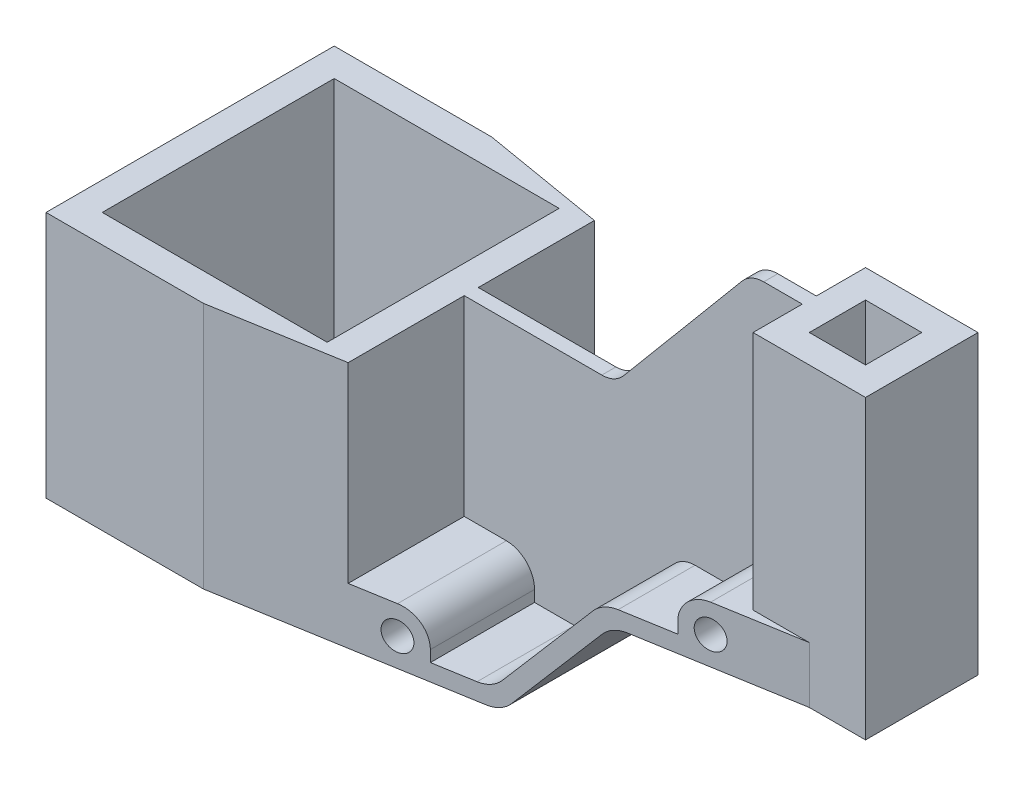
SolidWorks part; units mm, degrees
material "Alliage 1060"
ref_plane "Front Plane" through (0, 0, 0) normal (0, 0, 1) x (1, 0, 0)
ref_plane "Top Plane" through (0, 0, 0) normal (0, 1, 0) x (1, 0, 0)
ref_plane "Right Plane" through (0, 0, 0) normal (1, 0, 0) x (0, 0, -1)
sketch "Esquisse1" plane through (0, 0, 0) normal (0, 1, 0) x (1, 0, 0)
  line L0 (0, 0) -> (251.0912, 0) construction
  line L1 (-50, 51.25) -> (50, 51.25)
  line L2 (-50, 51.25) -> (-50, -51.25)
  line L3 (-50, -51.25) -> (50, -51.25)
  line L4 (50, 51.25) -> (50, -51.25)
  line L10 (-40, 41.25) -> (40, 41.25)
  line L11 (40, 41.25) -> (40, -41.25)
  line L12 (-40, -41.25) -> (40, -41.25)
  line L13 (-40, 41.25) -> (-40, -41.25)
  dimension "D1" = 51.25
  dimension "D2" = 51.25
  dimension "D3" = 100
  dimension "D4" = 50
  dimension "D9" = 10
extrude "Boss.-Extru.3" add sketch "Esquisse1" along normal blind 88
sketch "Esquisse3" plane through (0, 0, 51.25) normal (0, 0, 1) x (1, 0, 0)
  line L0 (50, 0) -> (96.6584, 0)
  line L1 (96.6584, 0) -> (130.2224, 40)
  line L2 (130.2224, 40) -> (190.2224, 40)
  line L3 (50, 6) -> (93.8606, 6)
  line L4 (93.8606, 6) -> (127.4246, 46)
  line L5 (127.4246, 46) -> (190.2224, 46)
  line L6 (190.2224, 46) -> (190.2224, 40)
  dimension "D1" = 6
  dimension "D2" = 130
  dimension "D3" = 40
  dimension "D4" = 60
extrude "Boss.-Extru.4" add sketch "Esquisse3" against normal up to surface (102.5 mm away) contours L6 L5 L4 L3 L0 L1 L2 up to face at (0, 44, -51.25)
sketch "Esquisse7" plane through (0, 40, 0) normal (0, -1, 0) x (1, 0, 0)
  line L0 (0, 0) -> (190.2224, 0) construction
  line L1 (190.2224, -51.25) -> (190.2224, 51.25) construction
  line L2 (180.2224, 10) -> (180.2224, -10)
  line L3 (170.2224, 20) -> (210.2224, 20)
  line L4 (170.2224, 20) -> (170.2224, -20)
  line L5 (170.2224, -20) -> (210.2224, -20)
  line L6 (210.2224, 20) -> (210.2224, -20)
  line L7 (170.2224, 20) -> (210.2224, -20) construction
  line L8 (170.2224, -20) -> (210.2224, 20) construction
  line L9 (180.2224, -10) -> (200.2224, -10)
  line L10 (200.2224, 10) -> (200.2224, -10)
  line L11 (180.2224, 10) -> (200.2224, 10)
  dimension "D1" = 40
  dimension "D2" = 40
  dimension "D3" = 10
extrude "Boss.-Extru.11" add sketch "Esquisse7" against normal blind 105.5
sketch "Esquisse13" plane through (0, 46, 0) normal (0, 1, 0) x (1, 0, 0)
  line L4 (180.2224, -10) -> (190.2224, -10)
  line L21 (180.2224, -10) -> (190.2224, -10)
  line L26 (190.2224, -10) -> (190.2224, 10)
  line L28 (190.2224, -10) -> (190.2224, 10)
  line L30 (190.2224, 10) -> (180.2224, 10)
  line L31 (190.2224, 10) -> (180.2224, 10)
  line L32 (180.2224, 10) -> (180.2224, -10)
  line L33 (180.2224, 10) -> (180.2224, -10)
  dimension "D1" = 0
extrude "Enlèv. mat.-Extru.9" cut sketch "Esquisse13" against normal up to next
sketch "Esquisse14" plane through (0, 0, 0) normal (0, 0, 1) x (1, 0, 0)
  line L0 (50, 88) -> (103.5971, 88)
  line L1 (103.5971, 88) -> (151.8453, 145.5)
  line L2 (151.8453, 145.5) -> (170.2224, 145.5)
  line L8 (93.8606, 6) -> (127.4246, 46) construction
  line L9 (50, 6) -> (93.8606, 6) construction
  line L10 (127.4246, 46) -> (170.2224, 46)
  line L15 (93.8606, 6) -> (127.4246, 46)
  line L16 (50, 6) -> (93.8606, 6)
  line L17 (170.2224, 46) -> (170.2224, 145.5)
  line L18 (50, 88) -> (50, 6)
  dimension "D1" = 45.25
extrude "Boss.-Extru.12" add sketch "Esquisse14" along normal mid plane 5
sketch "Esquisse17" plane through (0, 0, 0) normal (0, 0, 1) x (1, 0, 0)
  line L0 (-50, 88) -> (-50, 0) construction
  line L1 (-50, 0) -> (96.6584, 0) construction
  line L2 (210.2224, 145.5) -> (210.2224, 40) construction
  line L3 (130.2224, 40) -> (190.2224, 40) construction
  line L7 (44, 20) -> (44, 0)
  line L8 (44, 0) -> (75, 0)
  line L9 (75, 0) -> (75, 6)
  line L15 (190.2224, 40) -> (150.2224, 40)
  line L30 (50, 6) -> (93.8606, 6) construction
  line L36 (190.2224, 40) -> (190.2224, 60)
  line L37 (190.2224, 60) -> (150.2224, 60)
  line L38 (150.2224, 40) -> (150.2224, 60)
  line L39 (44, 20) -> (75, 20)
  line L42 (75, 20) -> (75, 6)
  circle A0 centre (65, 10) radius 5
  circle A1 centre (160.2224, 50) radius 5
  dimension "D9" = 10
  dimension "D2" = 10
  dimension "D3" = 115
  dimension "D4" = 10
  dimension "D5" = 50
  dimension "D6" = 10
  dimension "D7" = 10
  dimension "D8" = 10
  dimension "D10" = 20
extrude "Boss.-Extru.13" add sketch "Esquisse17" along normal mid plane 102.5
sketch "Esquisse18" plane through (0, 0, 2.5) normal (0, 0, 1) x (1, 0, 0)
  circle A1 centre (160.2224, 50) radius 5
  circle A2 centre (160.2224, 50) radius 5
  circle A3 centre (65, 10) radius 5
  circle A4 centre (65, 10) radius 5
  dimension "D1" = 0
  dimension "D2" = 0
extrude "Enlèv. mat.-Extru.12" cut sketch "Esquisse18" against normal through all both and the other way through all
sketch "Esquisse19" plane through (0, 60, 0) normal (0, 1, 0) x (1, 0, 0)
  line L4 (180.2224, 10) -> (180.2224, -10)
  line L5 (180.2224, -10) -> (190.2224, -10)
  line L6 (190.2224, -10) -> (190.2224, 10)
  line L7 (190.2224, 10) -> (180.2224, 10)
  line L8 (180.2224, 10) -> (180.2224, -10)
  line L9 (180.2224, -10) -> (190.2224, -10)
  line L10 (190.2224, -10) -> (190.2224, 10)
  line L11 (190.2224, 10) -> (180.2224, 10)
  dimension "D1" = 0
extrude "Enlèv. mat.-Extru.13" cut sketch "Esquisse19" against normal up to next
sketch "Esquisse20" plane through (0, 0, 0) normal (0, 1, 0) x (1, 0, 0)
  line L1 (50, 51.25) -> (-50, 51.25) construction
  line L2 (6, 51.25) -> (190.2224, 20)
  line L3 (170.2224, 20) -> (210.2224, 20) construction
  line L4 (190.2224, 20) -> (210.2224, 20)
  line L6 (210.2224, -20) -> (190.2224, -20)
  line L7 (190.2224, -20) -> (6, -51.25)
  line L8 (6, 51.25) -> (210.2224, 51.25)
  line L9 (210.2224, 51.25) -> (210.2224, 20)
  line L11 (6, -51.25) -> (210.2224, -51.25)
  line L12 (210.2224, -51.25) -> (210.2224, -20)
  line L13 (-50, -51.25) -> (50, -51.25) construction
fillet "Congé1" radius 10 12 edges at (75, 20, -26.875) (93.8606, 6, -26.875) (127.4246, 46, -26.875) (150.2224, 60, -26.875) (96.6584, 0, 0) (130.2224, 40, 0) (150.2224, 60, 26.875) (75, 20, 26.875) (93.8606, 6, 26.875) (127.4246, 46, 26.875) (151.8453, 145.5, 0) (103.5971, 88, 0)
extrude "Enlèv. mat.-Extru.15" cut sketch "Esquisse20" along normal up to surface (145.5 mm away)
equation "\"A\" = 205'a"
equation "\"B\"= 100'b"
equation "\"W\"= \"B\" / 2'w"
equation "\"X\"= \"A\" / 4'x"
equation "\"Y\"= \"B\" + 5.5'y"
equation "\"Z\"= \"B\" + 15'z"
equation "\"C\"= 40"
equation "\"D1@Esquisse1\"=\"X\""
equation "\"D2@Esquisse1\"=\"X\""
equation "\"D3@Esquisse1\"=\"B\""
equation "\"D4@Esquisse1\"=\"W\""
equation "\"D1@Boss.-Extru.11\"=\"Y\""
equation "\"D1@Esquisse14\"=\"X\"-6"
equation "\"D3@Esquisse17\"=\"Z\""
equation "\"D1@Boss.-Extru.13\"=\"X\"*2"
equation "\"D1@Enlèv. mat.-Extru.12\"=\"X\"+\"X\""
